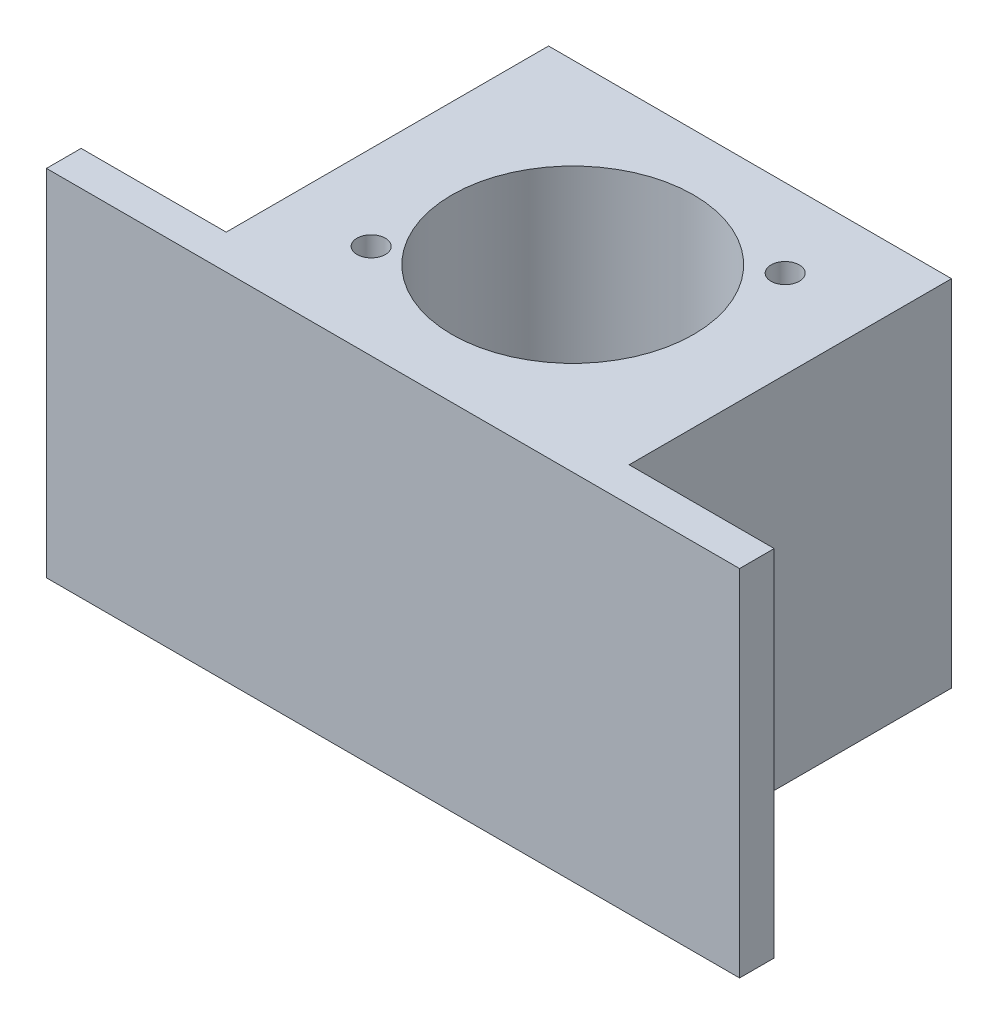
SolidWorks part; units mm, degrees
ref_plane "前视基准面" through (0, 0, 0) normal (0, 0, 1) x (1, 0, 0)
ref_plane "上视基准面" through (0, 0, 0) normal (0, 1, 0) x (1, 0, 0)
ref_plane "右视基准面" through (0, 0, 0) normal (1, 0, 0) x (0, 0, -1)
sketch "草图2" plane through (0, 0, 0) normal (0, 0, 1) x (1, 0, 0)
  line L1 (-107.5, 55) -> (107.5, 55)
  line L2 (-107.5, 55) -> (-107.5, -55)
  line L3 (-107.5, -55) -> (107.5, -55)
  line L4 (107.5, 55) -> (107.5, -55)
  line L5 (-107.5, 55) -> (107.5, -55) construction
  line L6 (-107.5, -55) -> (107.5, 55) construction
  point P0 (0, 0)
  dimension "D1" = 215
  dimension "D2" = 110
extrude "凸台-拉伸1" add sketch "草图2" against normal blind 30
sketch "草图3" plane through (0, 0, -30) normal (0, 0, -1) x (-1, 0, 0)
  line L1 (-62.5, 55) -> (62.5, 55)
  line L2 (-62.5, 55) -> (-62.5, -55)
  line L3 (-62.5, -55) -> (62.5, -55)
  line L4 (62.5, 55) -> (62.5, -55)
  line L5 (-62.5, 55) -> (62.5, -55) construction
  line L6 (-62.5, -55) -> (62.5, 55) construction
  point P0 (0, 0)
  dimension "D1" = 125
  dimension "D2" = 110
extrude "凸台-拉伸2" add sketch "草图3" along normal blind 100
sketch "草图4" plane through (0, 55, 0) normal (0, 1, 0) x (1, 0, 0)
  line L0 (-62.5, 130) -> (62.5, 130) construction
  circle A0 centre (0, 75) radius 37.5
  dimension "D2" = 75
  dimension "D1" = 55
extrude "切除-拉伸1" cut sketch "草图4" against normal through all
sketch "草图5" plane through (0, 55, 0) normal (0, 1, 0) x (1, 0, 0)
  line L17 (-97.5, 10) -> (97.5, 10)
  line L18 (-97.5, 20) -> (-97.5, 10)
  line L19 (-52.5, 20) -> (-97.5, 20)
  line L20 (-52.5, 120) -> (-52.5, 20)
  line L21 (52.5, 120) -> (-52.5, 120)
  line L22 (52.5, 20) -> (52.5, 120)
  line L23 (97.5, 20) -> (52.5, 20)
  line L24 (97.5, 10) -> (97.5, 20)
  line L25 (-97.5, 10) -> (97.5, 10)
  line L26 (-97.5, 20) -> (-97.5, 10)
  line L27 (-52.5, 20) -> (-97.5, 20)
  line L28 (-52.5, 120) -> (-52.5, 20)
  line L29 (52.5, 120) -> (-52.5, 120)
  line L30 (52.5, 20) -> (52.5, 120)
  line L31 (97.5, 20) -> (52.5, 20)
  line L32 (97.5, 10) -> (97.5, 20)
  circle A0 centre (0, 75) radius 55
  circle A1 centre (0, 75) radius 37.5 construction
  dimension "D1" = 110
  dimension "D2" = 10
sketch "草图6" plane through (0, 55, 0) normal (0, 1, 0) x (1, 0, 0)
sketch "草图7" plane through (0, 55, 0) normal (0, 1, 0) x (1, 0, 0)
  line L0 (62.5, 130) -> (0, 74.3529) construction
  line L2 (0, 74.3529) -> (-62.5, 30) construction
  circle A0 centre (0, 74.3529) radius 55
  point P2 (35.201, 105.6942)
  point P5 (-36.1939, 48.668)
sketch "草图8" plane through (0, -55, 0) normal (0, -1, 0) x (1, 0, 0)
  circle A0 centre (0, -74.4355) radius 55
hole_wizard "M10x1.25 螺纹孔2" positions "3D草图1" profile "草图9" tap size "M10x1.25" standard "AS"
sketch3d "3D草图1"
  point P0 (-36.1939, 55, -48.668)
  point P3 (35.201, 55, -105.6942)
sketch "草图9" plane through (-36.1939, 55, -48.668) normal (1, 0, 0) x (0, 0, 1)
  line L0 (0, 0) -> (0, 36)
  line L1 (0, 36) -> (4.4, 33.3562)
  line L2 (4.4, 33.3562) -> (4.4, 0)
  line L5 (4.4, 0) -> (0, 0)
  line L10 (0, 36) -> (-4.4, 33.3562) construction
  line L11 (0, -6.35) -> (0, 107.95) construction
  dimension "螺纹孔钻头直径" = 8.8
  dimension "螺纹孔钻头深度" = 36
  dimension "导头角度" = 118
cosmetic thread "孔螺蚊线1" parameters "D1"=20, "D2"=10
cosmetic thread "孔螺蚊线2" parameters "D1"=20, "D2"=10
pattern_linear "阵列(线性)1" count 2 spacing 110 along (0, 1, 0) of "M10x1.25 螺纹孔2"
sketch "草图14" plane through (0, 0, -30) normal (0, 0, -1) x (-1, 0, 0)
  line L0 (77.5, 45) -> (77.5, 25) construction
  line L1 (82.5, 45) -> (82.5, 25)
  line L2 (72.5, 45) -> (72.5, 25)
  line L3 (62.5, 55) -> (107.5, 55) construction
  line L4 (62.5, -55) -> (62.5, 55) construction
  line L5 (-72.5, 45) -> (-72.5, 25) construction
  line L6 (-67.5, 45) -> (-67.5, 25)
  line L7 (-77.5, 45) -> (-77.5, 25)
  line L8 (77.5, -25) -> (77.5, -45) construction
  line L9 (82.5, -25) -> (82.5, -45)
  line L10 (72.5, -25) -> (72.5, -45)
  line L11 (-72.5, -25) -> (-72.5, -45) construction
  line L12 (-67.5, -25) -> (-67.5, -45)
  line L13 (-77.5, -25) -> (-77.5, -45)
  line L14 (-62.5, -55) -> (-107.5, -55) construction
  arc A0 (82.5, 45) -> (72.5, 45) centre (77.5, 45) ccw
  arc A1 (72.5, 25) -> (82.5, 25) centre (77.5, 25) ccw
  arc A2 (-67.5, 45) -> (-77.5, 45) centre (-72.5, 45) ccw
  arc A3 (-77.5, 25) -> (-67.5, 25) centre (-72.5, 25) ccw
  arc A4 (82.5, -25) -> (72.5, -25) centre (77.5, -25) ccw
  arc A5 (72.5, -45) -> (82.5, -45) centre (77.5, -45) ccw
  arc A6 (-67.5, -25) -> (-77.5, -25) centre (-72.5, -25) ccw
  arc A7 (-77.5, -45) -> (-67.5, -45) centre (-72.5, -45) ccw
  point P2 (77.5, 35)
  point P14 (-72.5, 35)
  point P22 (77.5, -35)
  point P29 (-72.5, -35)
  dimension "D1" = 10
  dimension "D2" = 20
  dimension "D3" = 10
  dimension "D4" = 2
  dimension "1" = 10
  dimension "D6" = 20
  dimension "D5" = 2
sketch "草图15" [suppressed] plane through (0, -55, 0) normal (0, -1, 0) x (1, 0, 0)
  line L0 (34.7584, -46.8284) -> (4.6689, -79.6551) construction
  line L1 (4.6689, -79.6551) -> (-31.9137, -119.5657) construction
  circle A0 centre (34.7584, -46.8284) radius 5
  circle A1 centre (-25.8429, -112.9426) radius 5
extrude "切除-拉伸9" cut sketch "草图14" against normal blind 10
sketch "草图25" plane through (0, -55, 0) normal (0, -1, 0) x (-1, 0, 0)
  line L0 (-34.6882, 40.3746) -> (0, 75)
  line L1 (0, 75) -> (34.4238, 109.3615)
  circle A1 centre (-34.6882, 40.3746) radius 5.6987
  circle A2 centre (34.4238, 109.3615) radius 4.8079
  point P0 (-34.6882, 40.3746)
  point P7 (34.4238, 110.4056)
hole_wizard "M10x1.25 螺纹孔4" positions "草图25" profile "草图26" tap size "M10x1.25" standard "GB"
sketch "草图26" plane through (34.6882, -55, -40.3746) normal (1, 0, 0) x (0, 0, -1)
  line L0 (0, 0) -> (0, 36)
  line L1 (0, 36) -> (4.4, 33.3562)
  line L2 (4.4, 33.3562) -> (4.4, 0)
  line L5 (4.4, 0) -> (0, 0)
  line L10 (0, 36) -> (-4.4, 33.3562) construction
  line L11 (0, -6.35) -> (0, 107.95) construction
  dimension "螺纹孔钻头直径" = 8.8
  dimension "螺纹孔钻头深度" = 36
  dimension "导头角度" = 118
cosmetic thread "孔螺蚊线7" parameters "D1"=20, "D2"=10
cosmetic thread "孔螺蚊线8" parameters "D1"=20, "D2"=10
sketch "草图27" plane through (0, -55, 0) normal (0, -1, 0) x (1, 0, 0)
  line L0 (-62.5, -130) -> (-62.5, -129.25)
  line L1 (-62.5, -130) -> (-62.5, -30) construction
  line L2 (-62.5, -129.25) -> (62.5, -129.25)
  line L3 (62.5, -130) -> (62.5, -30) construction
  line L4 (62.5, -129.25) -> (62.5, -130)
  line L5 (62.5, -130) -> (-62.5, -130)
  dimension "D1" = 0.75
sketch "草图28" plane through (0, -55, 0) normal (0, -1, 0) x (1, 0, 0)
  line L0 (-107.5, 0) -> (-107.5, -19.25)
  line L1 (-107.5, -30) -> (-107.5, 0) construction
  line L2 (-107.5, -19.25) -> (107.5, -19.25)
  line L3 (107.5, -30) -> (107.5, 0) construction
  line L4 (107.5, -19.25) -> (107.5, 0)
  line L5 (107.5, 0) -> (-107.5, 0)
  dimension "D1" = 19.25
extrude "切除-拉伸11" cut sketch "草图28" against normal up to surface (110 mm away) up to face at (-36.1939, 55, -44.268)
